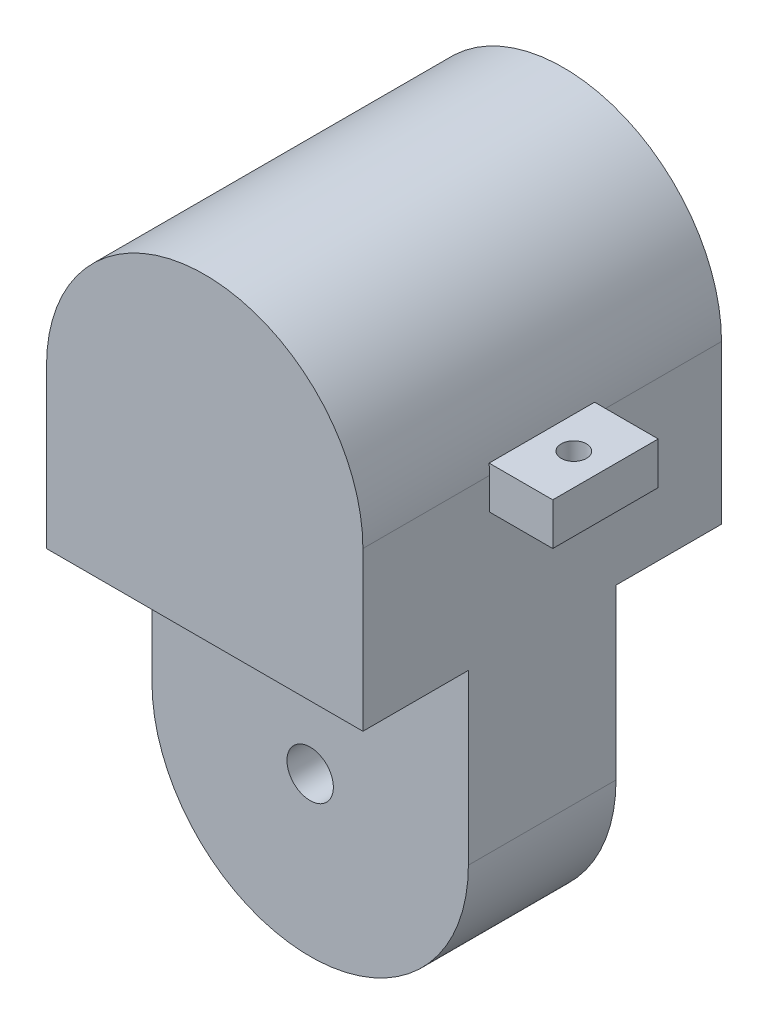
SolidWorks part; units mm, degrees
ref_plane "Front Plane" through (0, 0, 0) normal (0, 0, 1) x (1, 0, 0)
ref_plane "Top Plane" through (0, 0, 0) normal (0, 1, 0) x (1, 0, 0)
ref_plane "Right Plane" through (0, 0, 0) normal (1, 0, 0) x (0, 0, -1)
sketch "Finger_Skeleton" plane through (0, 0, 0) normal (0, 0, -1) x (-1, 0, 0)
  line L0 (0, 0) -> (0, 15.5)
  line L1 (0, 15.5) -> (0, 40.5)
  line L2 (0, 40.5) -> (0, 63.5)
  circle A1 centre (0, 0) radius 5 construction
  circle A2 centre (0, 15.5) radius 5 construction
  circle A3 centre (0, 40.5) radius 5 construction
  dimension "D4" = 10
  dimension "D5" = 10
  dimension "D6" = 10
  dimension "D1" = 15.5
  dimension "D2" = 25
  dimension "D3" = 23
sketch "Link1_Outline" plane through (0, 0, 0) normal (0, 0, 1) x (1, 0, 0)
  line L0 (0, 0) -> (0, 15.5) construction
  line L1 (-7.5, 0) -> (-7.5, 15.5)
  line L2 (7.5, 0) -> (7.5, 15.5)
  arc A0 (-7.5, 0) -> (7.5, 0) centre (0, 0) ccw
  arc A1 (7.5, 15.5) -> (-7.5, 15.5) centre (0, 15.5) ccw
  point P4 (0, 7.75)
  dimension "D1" = 15
extrude "Link1_Body" add sketch "Link1_Outline" along normal mid plane 17
sketch "Sketch1" plane through (7.5, 0, 0) normal (1, 0, 0) x (0, 0, -1)
  line L0 (0, 0) -> (0, 15.5) construction
  line L1 (3.5, -8) -> (9, -8)
  line L2 (3.5, -8) -> (3.5, 7.9981)
  line L3 (3.5, 7.9981) -> (9, 7.9981)
  line L4 (9, -8) -> (9, 7.9981)
  line L5 (-8.5, -7.5) -> (8.5, -7.5) construction
  line L6 (0, 9.9003) -> (0, -9.9003) construction
  line L7 (-9, -8) -> (-9, 7.9981)
  line L8 (-3.5, 7.9981) -> (-9, 7.9981)
  line L9 (-3.5, -8) -> (-3.5, 7.9981)
  line L10 (-3.5, -8) -> (-9, -8)
  dimension "D1" = 3.5
  dimension "D2" = 5.5
  dimension "D3" = 15.9981
  dimension "D4" = 0.5
extrude "Tongue_Cut" cut sketch "Sketch1" against normal through all both and the other way through all
sketch "Sketch2" plane through (0, 0, 0) normal (1, 0, 0) x (0, 0, -1)
  line L0 (0, 0) -> (0, 15.5) construction
  line L1 (3.8, 17) -> (-3.8, 17)
  line L2 (3.8, 17) -> (3.8, 35)
  line L3 (3.8, 35) -> (-3.8, 35)
  line L4 (-3.8, 17) -> (-3.8, 35)
  dimension "D1" = 3.8
  dimension "D2" = 18
  dimension "D3" = 7.6
  dimension "D4" = 17
sketch "Sketch3" plane through (0, 0, 0) normal (0, 0, 1) x (1, 0, 0)
  circle A0 centre (0, 0) radius 1.1
  dimension "D1" = 2.2
extrude "Pin_Holes" cut sketch "Sketch3" against normal through all both and the other way through all
sketch "Sketch4" plane through (0, 0, 0) normal (0, 0, 1) x (1, 0, 0)
  line L0 (0, 0) -> (0, 15.5) construction
  line L1 (7, 16) -> (10.5, 16)
  line L2 (7, 16) -> (7, 14)
  line L3 (7, 14) -> (10.5, 14)
  line L4 (10.5, 16) -> (10.5, 14)
  dimension "D1" = 7
  dimension "D2" = 3.5
  dimension "D3" = 14
  dimension "D4" = 2
extrude "Guide_Block_1" add sketch "Sketch4" along normal mid plane 5
sketch "Sketch5" plane through (0, 0, 0) normal (0, 0, 1) x (1, 0, 0)
  line L0 (0, 0) -> (0, 15.5) construction
  line L1 (7.0006, 32) -> (10.5006, 32)
  line L2 (7.0006, 32) -> (7.0006, 34)
  line L3 (7.0006, 34) -> (10.5006, 34)
  line L4 (10.5006, 32) -> (10.5006, 34)
  dimension "D1" = 7.0006
  dimension "D2" = 32
  dimension "D3" = 3.5
  dimension "D4" = 2
sketch "Sketch6" plane through (0, 0, 0) normal (0, 1, 0) x (1, 0, 0)
  line L1 (10.5, -2.5) -> (7.4833, -2.5) construction
  circle A0 centre (9, 0) radius 0.6
  dimension "D1" = 1.2
  dimension "D2" = 9
  dimension "D3" = 2.5
extrude "Cord_Guides" cut sketch "Sketch6" along normal through all both and the other way through all
